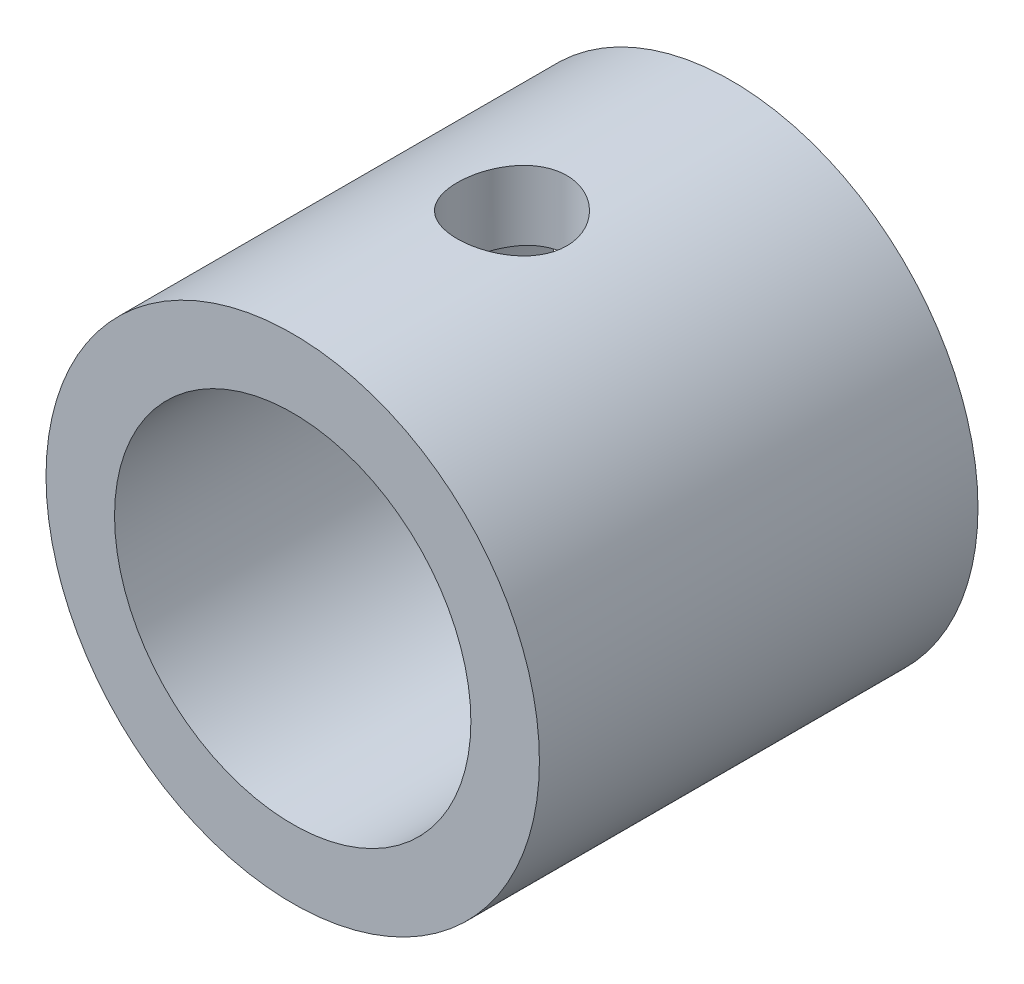
SolidWorks part; units mm, degrees
material "Aluminum Bronze"
ref_plane "Front Plane" through (0, 0, 0) normal (0, 0, 1) x (1, 0, 0)
ref_plane "Top Plane" through (0, 0, 0) normal (0, 1, 0) x (1, 0, 0)
ref_plane "Right Plane" through (0, 0, 0) normal (1, 0, 0) x (0, 0, -1)
sketch "Sketch1" plane through (0, 0, 0) normal (0, 0, 1) x (1, 0, 0)
  circle A0 centre (0, 0) radius 9
  circle A1 centre (0, 0) radius 6.5
  dimension "D1" = 18
  dimension "D2" = 13
extrude "Boss-Extrude1" add sketch "Sketch1" along normal mid plane 16
sketch "Sketch2" plane through (0, 0, 0) normal (0, 1, 0) x (1, 0, 0)
  circle A0 centre (0, 0) radius 2
  dimension "D1" = 4
extrude "Cut-Extrude1" cut sketch "Sketch2" along normal up to next
cosmetic thread "Cosmetic Thread1" parameters "D2"=5
